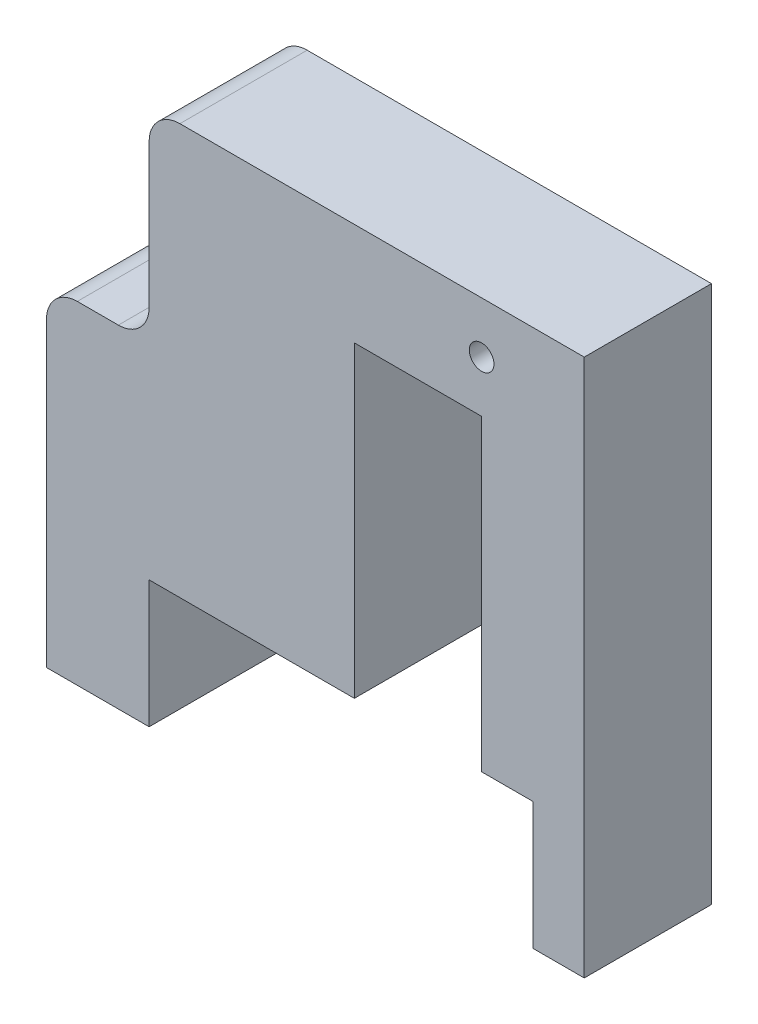
SolidWorks part; units mm, degrees
ref_plane "Front Plane" through (0, 0, 0) normal (0, 0, 1) x (1, 0, 0)
ref_plane "Top Plane" through (0, 0, 0) normal (0, 1, 0) x (1, 0, 0)
ref_plane "Right Plane" through (0, 0, 0) normal (1, 0, 0) x (0, 0, -1)
sketch "Model" plane through (0, 0, 0) normal (0, 0, 1) x (1, 0, 0)
  line L0 (47.4, 0) -> (52.4, 0)
  line L1 (0, 0) -> (10, 0)
  line L2 (0, 0) -> (0, 29.4)
  line L3 (13, 52.4) -> (52.4, 52.4)
  line L4 (52.4, 0) -> (52.4, 52.4)
  line L6 (10, 0) -> (10, 12.4)
  line L7 (10, 12.4) -> (30, 12.4)
  line L8 (47.4, 0) -> (47.4, 12.4)
  line L9 (42.4, 12.4) -> (47.4, 12.4)
  line L11 (3, 32.4) -> (7, 32.4)
  line L12 (10, 49.4) -> (10, 35.4)
  line L13 (30, 12.4) -> (30, 42.4)
  line L14 (30, 42.4) -> (42.4, 42.4)
  line L15 (42.4, 12.4) -> (42.4, 42.4)
  arc A0 (3, 32.4) -> (0, 29.4) centre (3, 29.4) ccw
  arc A1 (7, 32.4) -> (10, 35.4) centre (7, 35.4) ccw
  arc A2 (13, 52.4) -> (10, 49.4) centre (13, 49.4) ccw
  circle A3 centre (42.4, 47.4) radius 1.2
  dimension "D4" = 3
  dimension "D12" = 2.4
  dimension "D10" = 12.4
  dimension "D26" = 12.4
  dimension "D3" = 30
  dimension "D5" = 10
  dimension "D6" = 10
  dimension "D7" = 20
  dimension "D8" = 20
  dimension "D9" = 5
  dimension "D11" = 5
  dimension "D13" = 5
  dimension "D14" = 10
extrude "Boss-Extrude1" add sketch "Model" along normal blind 12.4
equation "\"tab-width-small\" = 20mm ' Width of the small version of the Tab"
equation "\"material-thickness\" = 12.4mm"
equation "\"D10@Model\" = \"material-thickness\""
equation "\"D26@Model\" = \"material-thickness\""
equation "\"D1@Boss-Extrude1\"= \"material-thickness\""
